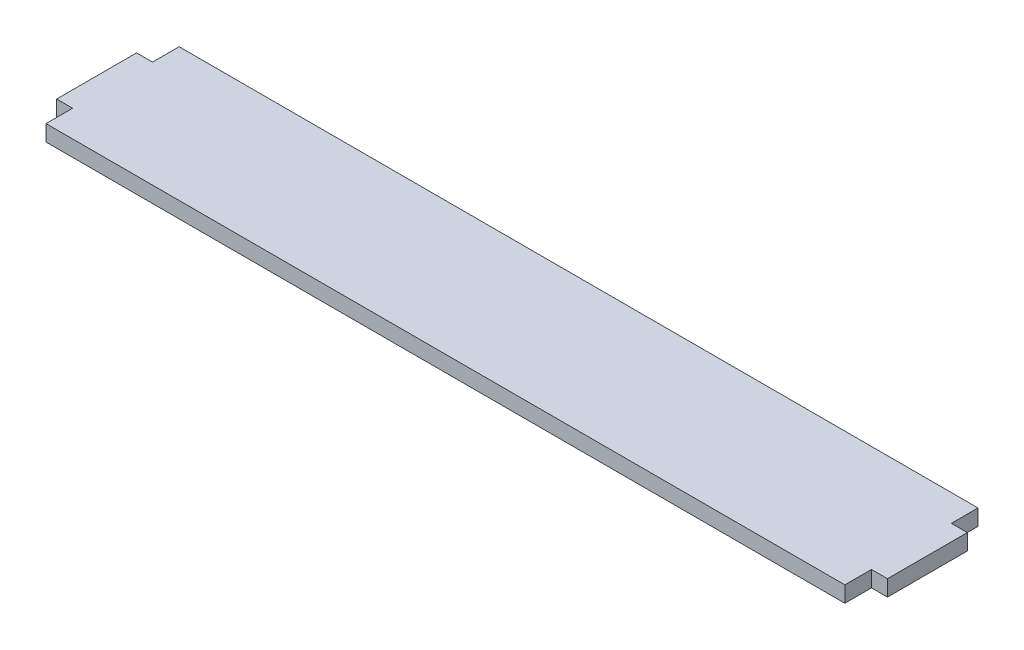
SolidWorks part; units mm, degrees
ref_plane "Alzado" through (0, 0, 0) normal (0, 0, 1) x (1, 0, 0)
ref_plane "Planta" through (0, 0, 0) normal (0, 1, 0) x (1, 0, 0)
ref_plane "Vista lateral" through (0, 0, 0) normal (1, 0, 0) x (0, 0, -1)
sketch "Croquis1" plane through (0, 0, 0) normal (0, 1, 0) x (1, 0, 0)
  line L0 (0, 5) -> (0, 0)
  line L1 (150, 25) -> (0, 25)
  line L2 (150, 25) -> (150, 20)
  line L3 (150, 0) -> (0, 0)
  line L4 (0, 25) -> (0, 20)
  line L5 (0, 20) -> (-3, 20)
  line L7 (0, 5) -> (-3, 5)
  line L8 (-3, 20) -> (-3, 5)
  line L9 (150, 20) -> (153, 20)
  line L11 (150, 5) -> (153, 5)
  line L12 (153, 20) -> (153, 5)
  line L13 (150, 5) -> (150, 0)
  dimension "D1" = 150
  dimension "D2" = 25
  dimension "D3" = 15
  dimension "D4" = 5
  dimension "D5" = 3
  dimension "D6" = 15
  dimension "D7" = 5
  dimension "D8" = 3
extrude "Saliente-Extruir1" add sketch "Croquis1" along normal blind 3
